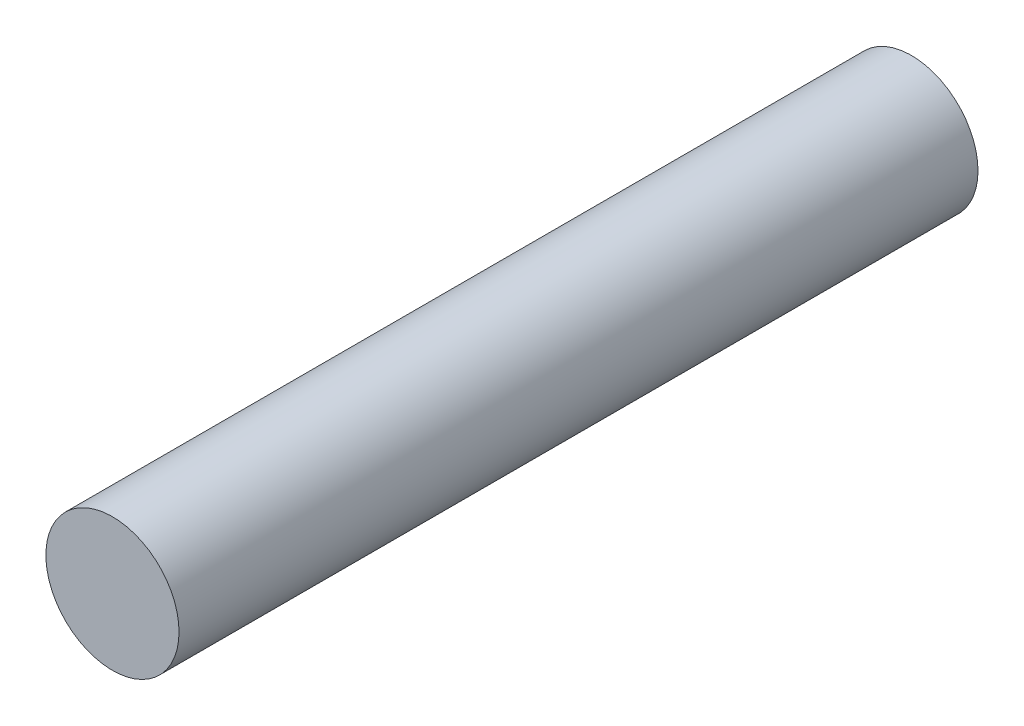
SolidWorks part; units mm, degrees
ref_plane "Front Plane" through (0, 0, 0) normal (0, 0, 1) x (1, 0, 0)
ref_plane "Top Plane" through (0, 0, 0) normal (0, 1, 0) x (1, 0, 0)
ref_plane "Right Plane" through (0, 0, 0) normal (1, 0, 0) x (0, 0, -1)
sketch "Sketch1" plane through (0, 0, 0) normal (0, 0, 1) x (1, 0, 0)
  circle A0 centre (0, 0) radius 25
extrude "Boss-Extrude1" add sketch "Sketch1" along normal blind 300
